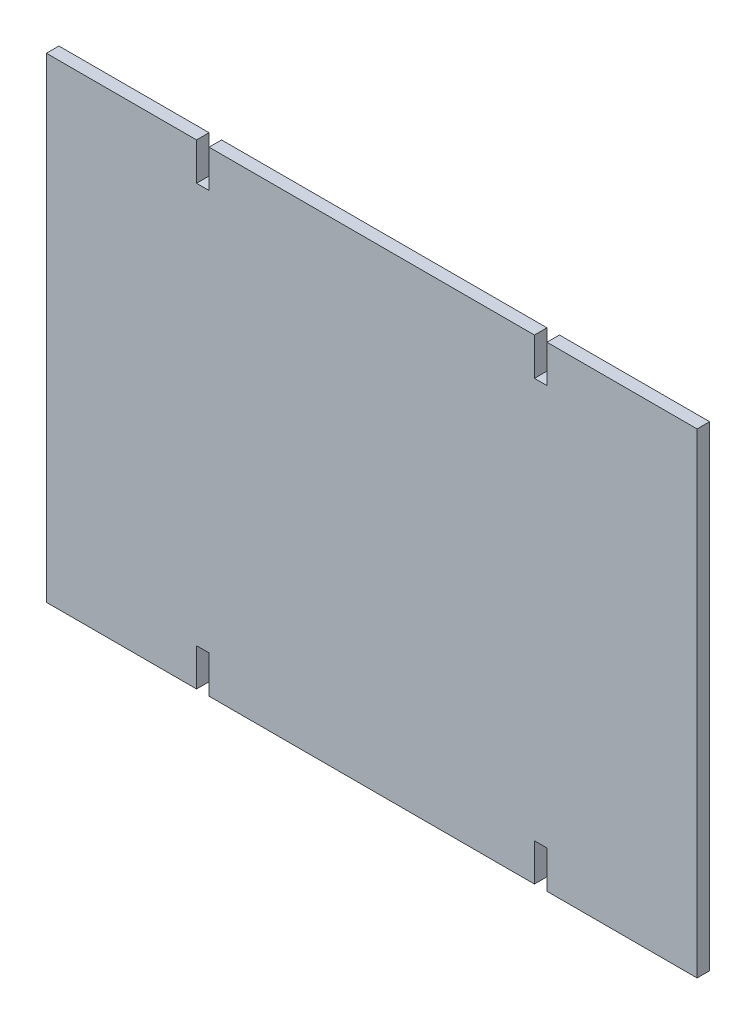
SolidWorks part; units mm, degrees
ref_plane "Front Plane" through (0, 0, 0) normal (0, 0, 1) x (1, 0, 0)
ref_plane "Top Plane" through (0, 0, 0) normal (0, 1, 0) x (1, 0, 0)
ref_plane "Right Plane" through (0, 0, 0) normal (1, 0, 0) x (0, 0, -1)
sketch "Sketch1" plane through (0, 0, 0) normal (0, 0, 1) x (1, 0, 0)
  line L1 (0, 0) -> (260, 0)
  line L2 (0, 0) -> (0, -190)
  line L3 (0, -190) -> (260, -190)
  line L4 (260, 0) -> (260, -190)
  dimension "D1" = 190
  dimension "D2" = 260
extrude "Boss-Extrude1" add sketch "Sketch1" along normal blind 5
sketch "Sketch2" plane through (0, 0, 0) normal (0, 0, -1) x (-1, 0, 0)
  line L0 (-260, 0) -> (0, 0) construction
  line L1 (-200, 0) -> (-195, 0)
  line L2 (-200, 0) -> (-200, -15)
  line L3 (-200, -15) -> (-195, -15)
  line L4 (-195, 0) -> (-195, -15)
  line L5 (-260, -190) -> (-260, 0) construction
  line L6 (-260, -95) -> (-214.0347, -95) construction
  line L7 (-195, -190) -> (-195, -175)
  line L8 (-200, -175) -> (-195, -175)
  line L9 (-200, -190) -> (-200, -175)
  line L10 (-200, -190) -> (-195, -190)
  line L11 (-130, 0) -> (-130, -36.439) construction
  line L12 (-65, 0) -> (-65, -15)
  line L13 (-60, -15) -> (-65, -15)
  line L14 (-60, 0) -> (-60, -15)
  line L15 (-60, 0) -> (-65, 0)
  line L16 (-60, -190) -> (-65, -190)
  line L17 (-60, -190) -> (-60, -175)
  line L18 (-60, -175) -> (-65, -175)
  line L19 (-65, -190) -> (-65, -175)
  dimension "D1" = 60
  dimension "D2" = 5
  dimension "D3" = 15
extrude "Cut-Extrude1" cut sketch "Sketch2" against normal blind 5
